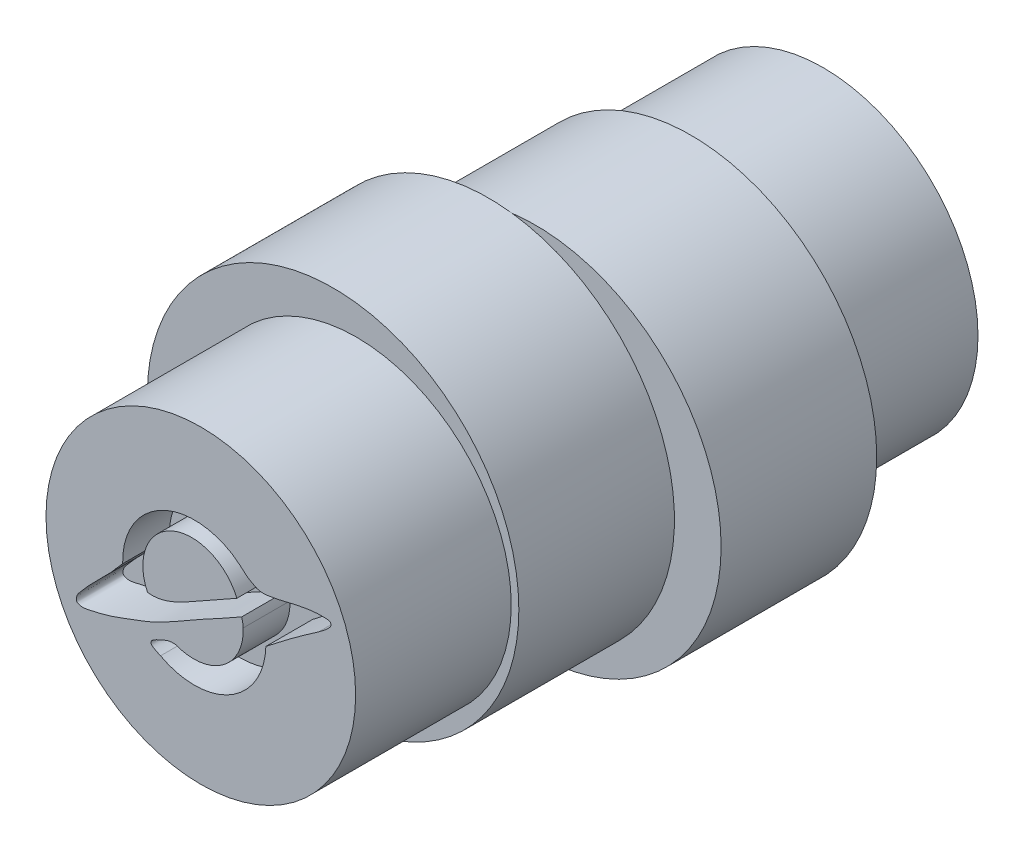
SolidWorks part; units mm, degrees
ref_plane "Front Plane" through (0, 0, 0) normal (0, 0, 1) x (1, 0, 0)
ref_plane "Top Plane" through (0, 0, 0) normal (0, 1, 0) x (1, 0, 0)
ref_plane "Right Plane" through (0, 0, 0) normal (1, 0, 0) x (0, 0, -1)
sketch "Sketch2" plane through (0, 0, 10.0549) normal (0, 0, 1) x (1, 0, 0)
  line L0 (2, 1.5) -> (2, -1.5)
  arc A0 (2, 1.5) -> (2, -1.5) centre (0, 0) ccw
  circle A1 centre (0, 0) radius 4.975
extrude "Boss-Extrude1" add sketch "Sketch2" along normal up to surface (5 mm away)
sketch "Sketch3" plane through (0, 0, 15.0549) normal (0, 0, 1) x (1, 0, 0)
  line L0 (2, 1.5) -> (2, -1.5)
  circle A0 centre (0.75, 0) radius 5.97
  arc A1 (2, 1.5) -> (2, -1.5) centre (0, 0) ccw
  point P0 (0.75, 0)
extrude "Boss-Extrude2" add sketch "Sketch3" along normal blind 5
sketch "Sketch5" plane through (0, 0, 20.0549) normal (0, 0, 1) x (1, 0, 0)
  line L0 (2, 1.5) -> (2, -1.5)
  arc A1 (2, 1.5) -> (2, -1.5) centre (0, 0) ccw
  circle A3 centre (-0.75, 0) radius 5.97
  point P0 (-0.75, 0)
extrude "Boss-Extrude3" add sketch "Sketch5" along normal blind 5
sketch "Sketch6" plane through (0, 0, 25.0549) normal (0, 0, 1) x (1, 0, 0)
  line L0 (2, 1.5) -> (2, -1.5)
  circle A0 centre (0, 0) radius 4.975
  arc A1 (2, 1.5) -> (2, -1.5) centre (0, 0) ccw
extrude "Boss-Extrude4" add sketch "Sketch6" along normal blind 5
sketch "Sketch8" plane through (0, 0, 25.4549) normal (0, 0, 1) x (1, 0, 0)
  circle A1 centre (0, 0) radius 2.6981
extrude "Boss-Extrude5" add sketch "Sketch8" along normal up to surface (4.6 mm away) up to face at (4.975, 0, 30.0549)
sketch "Sketch10" plane through (0, 0, 10.0549) normal (0, 0, -1) x (-1, 0, 0)
  line L0 (-2.1272, 1.5737) -> (-2.1272, -1.5737)
  line L5 (0, 0) -> (-2.1272, 0) construction
  arc A0 (-2.1272, -1.5737) -> (-2.1272, 1.5737) centre (0, 0) ccw
extrude "Cut-Extrude3" cut sketch "Sketch10" against normal blind 16.1
sketch "Sketch12" plane through (0, 0, 10.0549) normal (0, 0, -1) x (-1, 0, 0)
  circle A1 centre (0, 0) radius 2.646
extrude "Cut-Extrude4" cut sketch "Sketch12" against normal blind 3
sketch "Sketch13" plane through (0, 0, 30.0549) normal (0, 0, 1) x (1, 0, 0)
  line L0 (155, 475) -> (795, 475) construction
  arc A1 (-2.5112, -0.088) -> (1.0049, 1.9421) centre (-0.2026, -0.0264) cw
  arc A2 (2.0914, -0.088) -> (-1.2948, -2.0429) centre (-0.2062, -0.0184) cw
  arc A3 (1.3624, 0.0611) -> (-0.6376, -1.5427) centre (-0.2265, -0.0065) cw
  arc A4 (1.1574, 0.7837) -> (-1.7129, -0.487) centre (-0.2927, 0.182) ccw
  spline S0 degree 3 poles (1.3119, 0.3433) (1.2714, 0.3217) (0.9806, 0.1642) (0.4841, -0.131) (-0.1859, -0.473) (-0.8479, -0.873) (-1.5683, -1.2645) (-2.3378, -1.5361) (-3.0033, -1.7872) (-3.5021, -1.8983) (-3.8219, -1.9605) (-4.0176, -1.891) (-3.9879, -1.6778) (-3.8192, -1.4961) (-3.6096, -1.2387) (-3.3414, -0.9834) (-3.0916, -0.7136) (-2.7941, -0.4375) (-2.6288, -0.205) (-2.5112, -0.088) knots 0.239609 0.239609 0.239609 0.239609 0.252432 0.331937 0.400252 0.461906 0.547436 0.628009 0.688821 0.745647 0.769269 0.780801 0.795536 0.81781 0.851463 0.887179 0.921045 0.953844 1 1 1 1
  spline S1 degree 3 poles (1.0049, 1.9421) (1.0806, 1.8863) (1.1979, 1.808) (1.373, 1.6562) (1.4703, 1.5584) (1.5505, 1.513) knots 0 0 0 0 0.406231 0.607036 1 1 1 1
  spline S2 degree 3 poles (1.5505, 1.513) (1.6359, 1.4742) (1.773, 1.3663) (2.0391, 1.3344) (2.3319, 1.3881) (2.6667, 1.4468) (2.9822, 1.5411) (3.279, 1.5919) (3.5238, 1.6396) (3.784, 1.6574) (3.9698, 1.6597) (4.1689, 1.6441) (4.2024, 1.5284) (4.1263, 1.4473) (4.0104, 1.3359) (3.9683, 1.2912) (3.7923, 1.1681) knots 0 0 0 0 0.086754 0.154448 0.23846 0.35965 0.466365 0.540244 0.635675 0.696062 0.776342 0.817536 0.854233 0.891998 0.906575 1 1 1 1
  spline S3 degree 2 poles (2.0914, -0.088) (2.9261, 0.5752) (3.7923, 1.1681) knots 0 0 0 1 1 1
  spline S4 degree 3 poles (-1.2948, -2.0429) (-1.7469, -1.8487) (-1.7117, -1.7626) (-1.1175, -1.5233) knots 0 0 0 0 1 1 1 1
  spline S5 degree 2 poles (-1.1175, -1.5233) (-0.8516, -1.4338) (-0.6376, -1.5427) knots 0 0 0 1 1 1
  spline S7 degree 3 poles (-1.7129, -0.487) (-1.3845, -0.5325) (-0.9925, -0.4116) (-0.5179, -0.1589) knots 0 0 0 0 1 1 1 1
  spline S8 degree 2 poles (-0.5179, -0.1589) (0.3209, 0.3103) (1.1574, 0.7837) knots 0 0 0 1 1 1
  spline S9 degree 2 poles (1.3624, 0.0611) (1.355, 0.2057) (1.3119, 0.3433) knots 0 0 0 1 1 1
extrude "Cut-Extrude5" cut sketch "Sketch13" against normal blind 1.5
